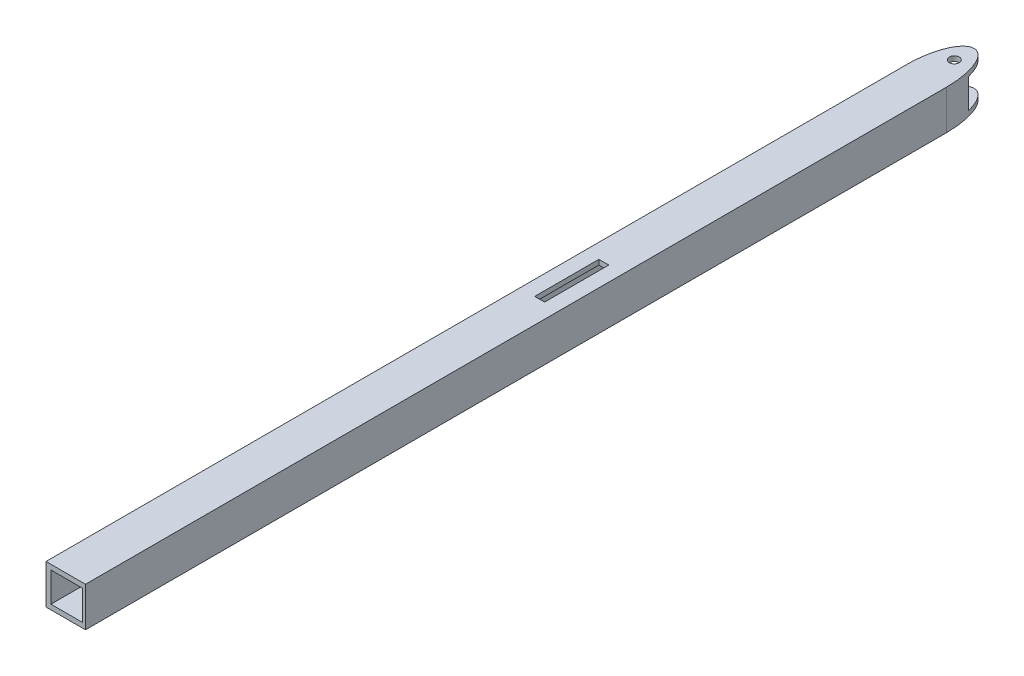
SolidWorks part; units mm, degrees
ref_plane "Front Plane" through (0, 0, 0) normal (0, 0, 1) x (1, 0, 0)
ref_plane "Top Plane" through (0, 0, 0) normal (0, 1, 0) x (1, 0, 0)
ref_plane "Right Plane" through (0, 0, 0) normal (1, 0, 0) x (0, 0, -1)
sketch "Sketch1" plane through (0, 0, 0) normal (0, 0, 1) x (1, 0, 0)
  line L1 (0, 0) -> (25.4, 0)
  line L2 (0, 0) -> (0, 25.4)
  line L3 (0, 25.4) -> (25.4, 25.4)
  line L4 (25.4, 0) -> (25.4, 25.4)
  dimension "D1" = 25.4
  dimension "D2" = 25.4
extrude "Boss-Extrude2" add sketch "Sketch1" along normal blind 584.2 contours L3 L4 L1 L2
sketch "Sketch2" plane through (0, 0, 0) normal (0, 0, -1) x (-1, 0, 0)
  line L0 (-23.4778, 22.225) -> (-3.175, 22.225)
  line L1 (-23.4778, 22.225) -> (-23.4778, 3.175)
  line L2 (-23.4778, 3.175) -> (-3.175, 3.175)
  line L3 (-3.175, 22.225) -> (-3.175, 3.175)
  line L4 (0, 0) -> (0, 25.4) construction
  line L5 (0, 0) -> (-25.4, 0) construction
  dimension "D1" = 3.175
  dimension "D2" = 3.175
extrude "Cut-Extrude1" cut sketch "Sketch2" against normal through all
sketch "Sketch3" plane through (0, 25.4, 0) normal (0, 1, 0) x (1, 0, 0)
  line L4 (0, 0) -> (25.4, 0) construction
  line L5 (12.7, 0) -> (25.4, 0)
  line L6 (25.4, 0) -> (25.4, -30.4659)
  line L7 (12.7, 0) -> (0, 0)
  line L8 (0, 0) -> (0, -30.4659)
  ellipse E0 centre (12.7, -30.4659) end of major axis (12.7, 0) minor radius 12.7 (25.4, -30.4659) -> (0, -30.4659) ccw
  line M2 (25.4, 0) -> (0, 0)
  line M3 (0, 0) -> (0, -584.2)
  line M5 (25.4, -584.2) -> (25.4, 0)
extrude "Cut-Extrude2" cut sketch "Sketch3" against normal through all contours E0 M2 M3 | E0 M5 M2
sketch "Sketch4" plane through (0, 25.4, 0) normal (0, 1, 0) x (1, 0, 0)
  line L0 (25.4, -584.2) -> (0, -584.2)
  line L2 (9.525, -279.4) -> (15.875, -279.4)
  line L4 (9.525, -279.4) -> (9.525, -238.1212)
  line L6 (15.875, -279.4) -> (15.875, -238.1212)
  line L7 (9.525, -238.1212) -> (15.875, -238.1212)
  dimension "D1" = 41.2788
  dimension "D2" = 6.35
sketch "Sketch6" plane through (0, 25.4, 0) normal (0, 1, 0) x (1, 0, 0)
  line L0 (0, 0) -> (25.4, 0)
  circle A0 centre (12.7, -12.7) radius 3.175
  circle A1 centre (12.7, -1206.5) radius 3.175
  point P7 (12.7, 0)
  dimension "D2" = 6.35
  dimension "D3" = 12.7
  dimension "D4" = 6.35
  dimension "D5" = 1206.5
  dimension "D1" = 25.4
extrude "Cut-Extrude5" cut sketch "Sketch6" against normal through all contours A0
extrude "Cut-Extrude6" cut sketch "Sketch4" against normal through all
